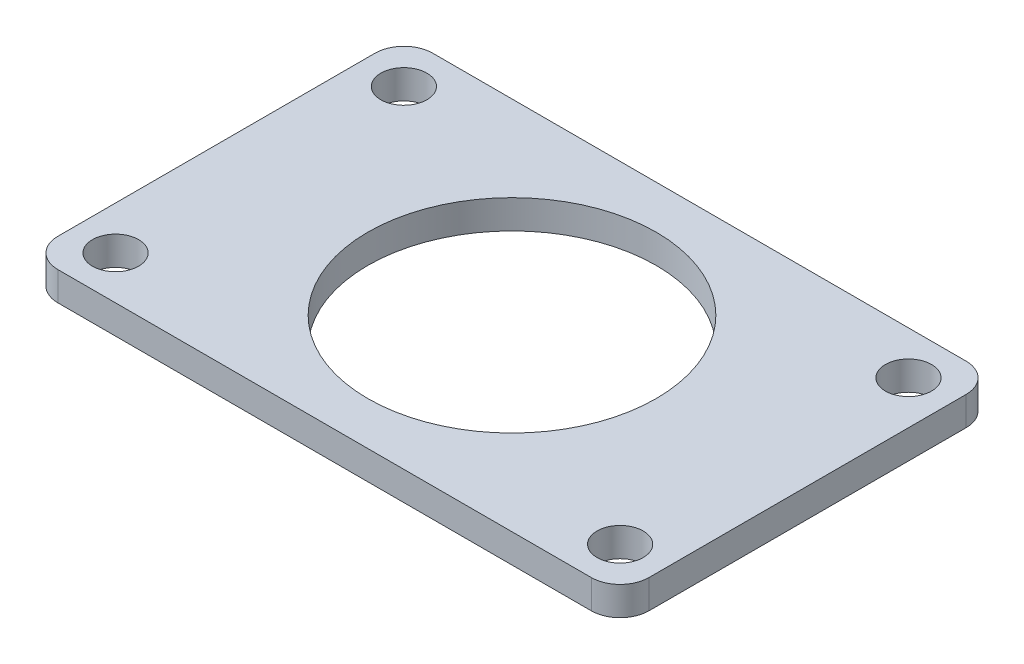
SolidWorks part; units mm, degrees
material "S-玻璃纤维"
ref_plane "前视基准面" through (0, 0, 0) normal (0, 0, 1) x (1, 0, 0)
ref_plane "上视基准面" through (0, 0, 0) normal (0, 1, 0) x (1, 0, 0)
ref_plane "右视基准面" through (0, 0, 0) normal (1, 0, 0) x (0, 0, -1)
sketch "草图1" plane through (0, 0, 0) normal (0, 1, 0) x (1, 0, 0)
  line L0 (-20.5, 13) -> (20.5, 13)
  line L1 (-17.5, 10) -> (17.5, 10) construction
  line L2 (-17.5, 10) -> (-17.5, -10) construction
  line L3 (-17.5, -10) -> (17.5, -10) construction
  line L4 (17.5, 10) -> (17.5, -10) construction
  line L5 (-17.5, 10) -> (17.5, -10) construction
  line L6 (-17.5, -10) -> (17.5, 10) construction
  line L11 (20.5, 13) -> (20.5, -13)
  line L12 (-20.5, -13) -> (20.5, -13)
  line L13 (-20.5, 13) -> (-20.5, -13)
  circle A0 centre (-17.5, 10) radius 1.6
  circle A1 centre (17.5, 10) radius 1.6
  circle A2 centre (17.5, -10) radius 1.6
  circle A3 centre (-17.5, -10) radius 1.6
  circle A4 centre (0, 0) radius 10
  point P0 (0, 0)
  point P6 (0, 0)
  dimension "D4" = 3.2
  dimension "D5" = 20
  dimension "D1" = 35
  dimension "D2" = 20
  dimension "D3" = 3
extrude "凸台-拉伸1" add sketch "草图1" along normal blind 2
fillet "圆角1" radius 2 4 edges at (20.5, 1, -13) (20.5, 1, 13) (-20.5, 1, 13) (-20.5, 1, -13)
